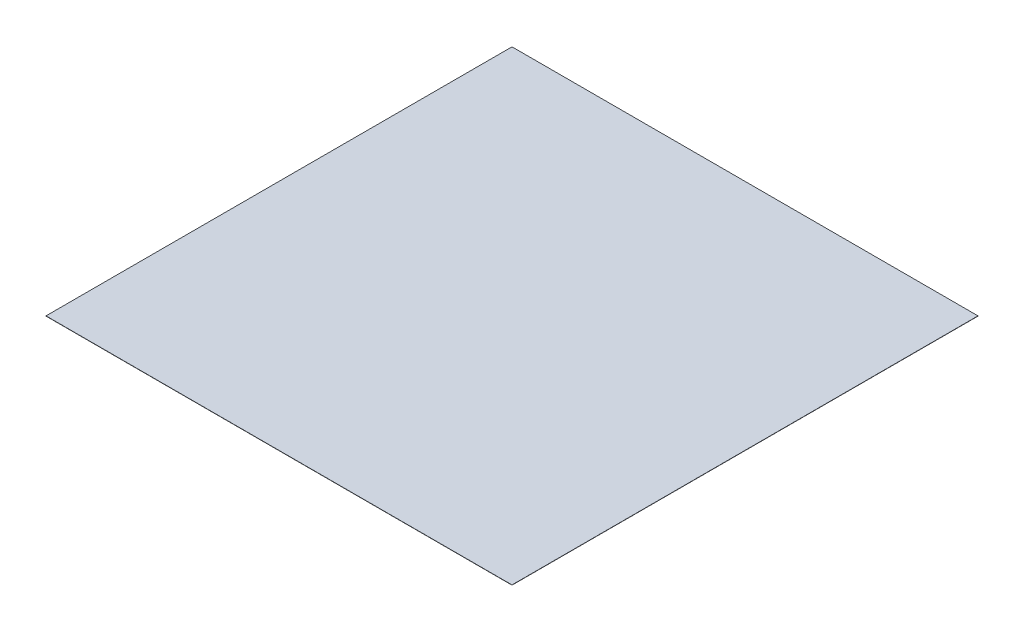
SolidWorks part; units mm, degrees
ref_plane "Front Plane" through (0, 0, 0) normal (0, 0, 1) x (1, 0, 0)
ref_plane "Top Plane" through (0, 0, 0) normal (0, 1, 0) x (1, 0, 0)
ref_plane "Right Plane" through (0, 0, 0) normal (1, 0, 0) x (0, 0, -1)
sketch "Sketch1" plane through (0, 0, 0) normal (0, 1, 0) x (1, 0, 0)
  line L1 (-5000, -5000) -> (5000, -5000)
  line L2 (-5000, -5000) -> (-5000, 5000)
  line L3 (-5000, 5000) -> (5000, 5000)
  line L4 (5000, -5000) -> (5000, 5000)
  line L5 (-5000, -5000) -> (5000, 5000) construction
  line L6 (-5000, 5000) -> (5000, -5000) construction
  point P0 (0, 0)
  dimension "D1" = 10000
  dimension "D2" = 10000
extrude "Boss-Extrude1" add sketch "Sketch1" along normal blind 5
